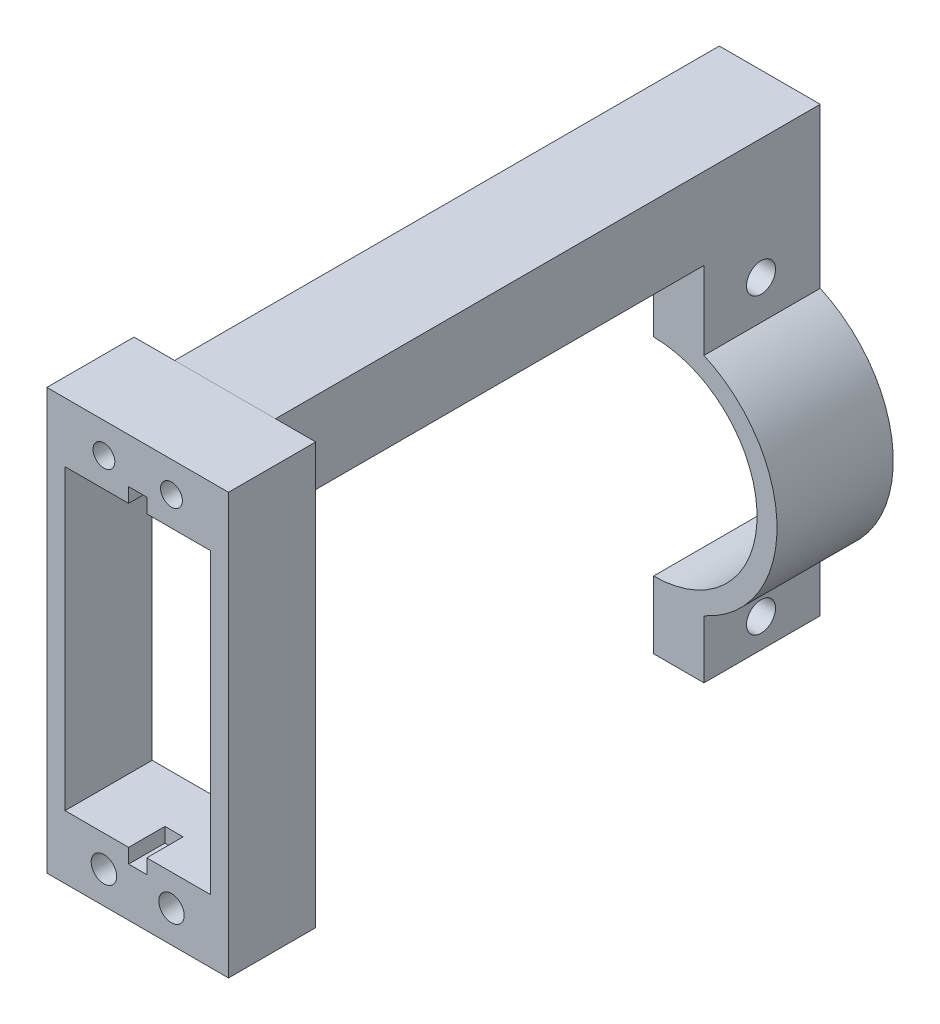
SolidWorks part; units mm, degrees
ref_plane "前基準面" through (0, 0, 0) normal (0, 0, 1) x (1, 0, 0)
ref_plane "上基準面" through (0, 0, 0) normal (0, 1, 0) x (1, 0, 0)
ref_plane "右基準面" through (0, 0, 0) normal (1, 0, 0) x (0, 0, -1)
sketch "草圖14" plane through (0, 0, -8) normal (0, 0, -1) x (-1, 0, 0)
  line L0 (-9.2398, 48.8622) -> (4.6523, 48.8622)
  line L1 (-12.2938, 48.8622) -> (7.7062, 48.8622) construction
  line L2 (4.6523, 48.8622) -> (4.6523, 56.9695)
  line L3 (10.2159, 56.9695) -> (-14.7841, 56.9695) construction
  line L4 (4.6523, 56.9695) -> (-9.2398, 56.9695)
  line L5 (-2.2938, 48.8622) -> (-2.2938, 75.1687) construction
  line L6 (-9.2398, 48.8622) -> (-9.2398, 56.9695)
  point P10 (-2.2938, 56.9695)
extrude "填料-伸長7" add sketch "草圖14" along normal blind 75
sketch "草圖15" plane through (0, 48.8622, 0) normal (0, -1, 0) x (1, 0, 0)
  line L0 (2.2938, -83) -> (2.2938, -44.5349) construction
  line L1 (9.2398, -83) -> (-4.6523, -83) construction
  line L2 (2.2938, -83) -> (-4.6523, -83)
  line L3 (-4.6523, -83) -> (-4.6523, -77)
  line L4 (-4.6523, -83) -> (-4.6523, -8) construction
  line L5 (-4.6523, -77) -> (2.2938, -77)
  line L6 (2.2938, -83) -> (9.2398, -83)
  line L7 (9.2398, -83) -> (9.2398, -77)
  line L8 (9.2398, -83) -> (9.2398, -8) construction
  line L9 (9.2398, -77) -> (2.2938, -77)
  dimension "D1" = 6
extrude "填料-伸長15" add sketch "草圖15" along normal blind 12 contours L5 L9 L7 L6 L2 L3
sketch "草圖21" plane through (0, 0, -77) normal (0, 0, 1) x (1, 0, 0)
  line L0 (-4.6523, 36.8622) -> (9.2398, 36.8622) construction
  line L1 (2.2938, 48.8622) -> (2.2938, 16.3048) construction
  line L3 (9.2398, 48.8622) -> (-4.6523, 48.8622) construction
  circle A0 centre (2.2938, 22.6122) radius 14.25
  circle A1 centre (2.2938, 22.6122) radius 17
  dimension "D1" = 28.5
  dimension "D2" = 34
extrude "填料-伸長16" add sketch "草圖21" against normal blind 6
sketch "草圖22" plane through (0, 0, -77) normal (0, 0, 1) x (1, 0, 0)
  line L0 (2.2938, 36.8622) -> (2.2938, -13.8606) construction
  line L1 (9.2398, 45.9683) -> (9.2398, -19.8476) construction
  line L2 (9.2398, 38.1284) -> (9.2398, 48.8622) construction
  line L3 (-4.6523, 41.8383) -> (-4.6523, -8.4361) construction
  line L4 (-4.6523, 38.1284) -> (-4.6523, 48.8622) construction
  line L5 (-4.6523, 7.096) -> (-4.6523, -0.904)
  line L6 (-4.6523, -0.904) -> (9.2398, -0.904)
  line L7 (9.2398, -0.904) -> (9.2398, 7.096)
  circle A0 centre (2.2938, 22.6122) radius 14.25 construction
  arc A2 (-4.6523, 38.1284) -> (9.2398, 38.1284) centre (2.2938, 22.6122) ccw construction
  arc A3 (-4.6523, 7.096) -> (9.2398, 7.096) centre (2.2938, 22.6122) ccw
  dimension "D1" = 8
extrude "填料-伸長17" add sketch "草圖22" against normal blind 6
sketch "草圖23" plane through (0, 0, -77) normal (0, 0, 1) x (1, 0, 0)
  line L0 (2.2938, 48.8622) -> (2.2938, 36.8622)
  line L1 (9.2398, 48.8622) -> (-4.6523, 48.8622) construction
  line L2 (2.2938, 48.8622) -> (-4.6523, 48.8622)
  line L3 (-4.6523, 48.8622) -> (-4.6523, 38.1284)
  line L4 (2.2938, -0.904) -> (2.2938, 8.3622)
  line L5 (-4.6523, -0.904) -> (9.2398, -0.904) construction
  line L6 (2.2938, -0.904) -> (-4.6523, -0.904)
  line L7 (-4.6523, -0.904) -> (-4.6523, 7.096)
  circle A0 centre (2.2938, 22.6122) radius 14.25 construction
  arc A1 (-4.6523, 38.1284) -> (-4.6523, 7.096) centre (2.2938, 22.6122) ccw
  arc A2 (2.2938, 36.8622) -> (2.2938, 8.3622) centre (2.2938, 22.6122) ccw
extrude "除料-伸長3" cut sketch "草圖23" against normal blind 6
sketch "草圖24" plane through (9.2398, 0, 0) normal (1, 0, 0) x (0, 0, -1)
  line L6 (77, -0.904) -> (83, -0.904) construction
sketch "草圖25" plane through (0, 0, -77) normal (0, 0, 1) x (1, 0, 0)
  line L0 (2.2938, -0.904) -> (9.2398, -0.904)
  line L1 (9.2398, -0.904) -> (9.2398, 7.096)
  line L2 (9.2398, 48.8622) -> (9.2398, 38.1284)
  line L3 (2.2938, 48.8622) -> (9.2398, 48.8622)
  line L4 (2.2938, 36.8622) -> (2.2938, 48.8622)
  line L5 (2.2938, 8.3622) -> (2.2938, -0.904)
  arc A0 (9.2398, 38.1284) -> (9.2398, 7.096) centre (2.2938, 22.6122) cw
  arc A1 (2.2938, 36.8622) -> (2.2938, 8.3622) centre (2.2938, 22.6122) cw
extrude "填料-伸長18" add sketch "草圖25" along normal blind 10
sketch "草圖26" plane through (9.2398, 0, 0) normal (1, 0, 0) x (0, 0, -1)
  circle A3 centre (74.8538, 3.096) radius 2
  circle A4 centre (74.8538, 43.4953) radius 2
  dimension "D1" = 4
  dimension "D2" = 4
extrude "除料-伸長5" cut sketch "草圖26" against normal through all
sketch "草圖27" plane through (0, 0, -8) normal (0, 0, 1) x (1, 0, 0)
  line L0 (-10.2062, 58.096) -> (14.7938, 58.096)
  line L1 (14.7938, 58.096) -> (14.7938, -0.904)
  line L2 (14.7938, -0.904) -> (-10.2062, -0.904)
  line L3 (-10.2062, -0.904) -> (-10.2062, 58.096)
  line L4 (-7.7062, 51.896) -> (12.2938, 51.896)
  line L6 (12.2938, 51.896) -> (12.2938, 10.896)
  line L7 (-7.7062, 51.896) -> (-7.7062, 10.896)
  line L8 (-7.7062, 10.896) -> (12.2938, 10.896)
  circle A0 centre (-2.3562, 6.596) radius 1.75
  circle A1 centre (6.9438, 6.596) radius 1.75
  circle A2 centre (-2.3562, 55.896) radius 1.5
  circle A3 centre (6.9438, 55.896) radius 1.5
  point P2 (2.2938, -0.904)
  dimension "D3" = 3.5
  dimension "D4" = 3.5
  dimension "D5" = 3
  dimension "D6" = 3
  dimension "D14" = 6.2
  dimension "D1" = 25
  dimension "D2" = 59
  dimension "D7" = 9.3
  dimension "D8" = 9.3
  dimension "D9" = 49.3
  dimension "D10" = 20
  dimension "D11" = 41
  dimension "D12" = 7.85
  dimension "D13" = 2.5
  dimension "D15" = 4
extrude "填料-伸長20" add sketch "草圖27" along normal blind 12
sketch "草圖28" plane through (0, 0, -8) normal (0, 0, 1) x (1, 0, 0)
  circle A0 centre (-2.3562, 55.896) radius 1.75
  circle A1 centre (6.9438, 55.896) radius 1.75
sketch "草圖29" plane through (0, 58.096, 0) normal (0, 1, 0) x (1, 0, 0)
  line L0 (-10.2062, 8) -> (-10.2062, -4)
  line L1 (-10.2062, -4) -> (14.7938, -4)
  line L2 (14.7938, -4) -> (14.7938, 8)
  line L3 (14.7938, 8) -> (-10.2062, 8)
extrude "填料-伸長21" add sketch "草圖29" along normal blind 2
sketch "草圖30" plane through (0, 0, -8) normal (0, 0, 1) x (1, 0, 0)
  line L0 (9.2398, 51.896) -> (-4.6523, 51.896)
  line L1 (-4.6523, 51.896) -> (-4.6523, 48.8622)
  line L2 (-4.6523, 48.8622) -> (9.2398, 48.8622)
  line L3 (9.2398, 48.8622) -> (9.2398, 51.896)
sketch "草圖31" plane through (0, 56.9695, 0) normal (0, 1, 0) x (1, 0, 0)
  line L0 (9.2398, 83) -> (-4.6523, 83)
  line L1 (-4.6523, 83) -> (-4.6523, 8)
  line L2 (-4.6523, 8) -> (9.2398, 8)
  line L3 (9.2398, 8) -> (9.2398, 83)
extrude "填料-伸長22" add sketch "草圖31" along normal blind 3.1
sketch "草圖33" plane through (0, -0.904, 0) normal (0, -1, 0) x (1, 0, 0)
  line L0 (-10.2062, 4) -> (14.7938, 4)
  line L1 (14.7938, 4) -> (14.7938, -8)
  line L2 (14.7938, -8) -> (-10.2062, -8)
  line L3 (-10.2062, -8) -> (-10.2062, 4)
extrude "除料-伸長8" cut sketch "草圖33" against normal blind 3.1
sketch "草圖34" plane through (0, 0, -8) normal (0, 0, 1) x (1, 0, 0)
  circle A0 centre (6.9438, 55.896) radius 1.5
  circle A1 centre (-2.3562, 55.896) radius 1.5
  dimension "D1" = 3
  dimension "D2" = 3
extrude "除料-伸長9" cut sketch "草圖34" against normal blind 7
sketch "草圖35" plane through (0, 0, 4) normal (0, 0, 1) x (1, 0, 0)
  line L0 (1.0438, 51.896) -> (3.5438, 51.896)
  line L1 (12.2938, 51.896) -> (-7.7062, 51.896) construction
  line L2 (1.0438, 51.896) -> (1.0438, 53.896)
  line L3 (1.0438, 53.896) -> (3.5438, 53.896)
  line L4 (3.5438, 53.896) -> (3.5438, 51.896)
  line L5 (1.0438, 10.896) -> (3.5438, 10.896)
  line L6 (-7.7062, 10.896) -> (12.2938, 10.896) construction
  line L7 (1.0438, 10.896) -> (1.0438, 8.896)
  line L8 (1.0438, 8.896) -> (3.5438, 8.896)
  line L9 (3.5438, 8.896) -> (3.5438, 10.896)
  point P5 (2.2938, 51.896)
  point P12 (2.2938, 10.896)
  dimension "D1" = 2.5
  dimension "D2" = 2
  dimension "D3" = 2.5
  dimension "D4" = 2
extrude "除料-伸長10" cut sketch "草圖35" against normal blind 5
